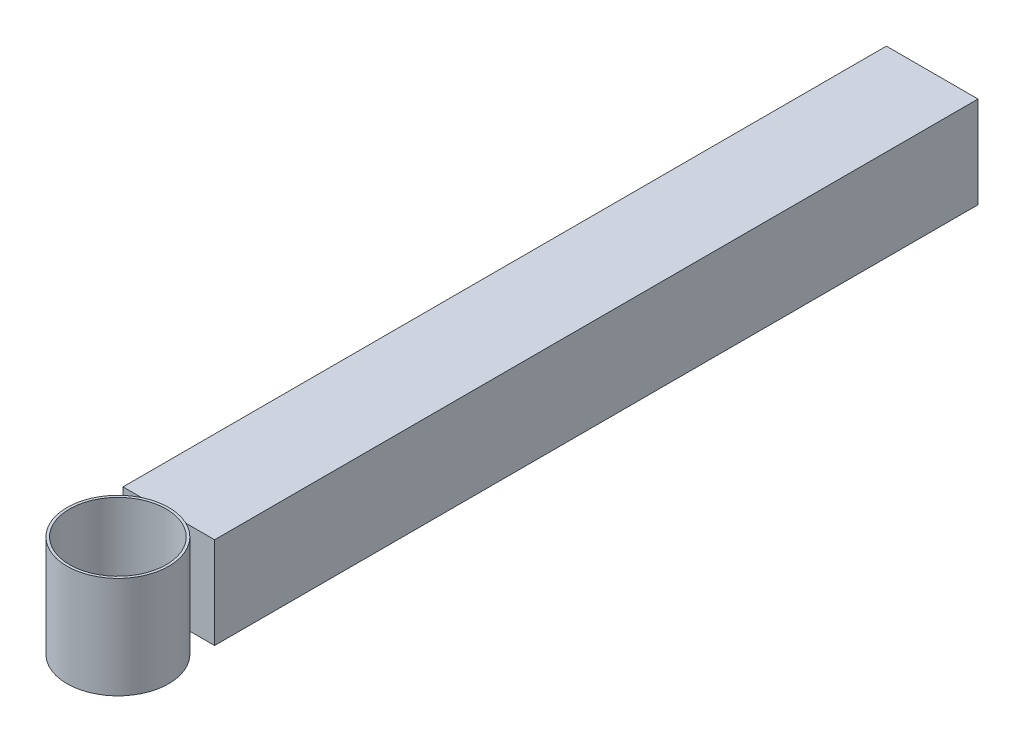
SolidWorks part; units mm, degrees
ref_plane "Front Plane" through (0, 0, 0) normal (0, 0, 1) x (1, 0, 0)
ref_plane "Top Plane" through (0, 0, 0) normal (0, 1, 0) x (1, 0, 0)
ref_plane "Right Plane" through (0, 0, 0) normal (1, 0, 0) x (0, 0, -1)
sketch "Sketch1" plane through (0, 0, 0) normal (0, 0, 1) x (1, 0, 0)
  line L1 (-18, -18) -> (18, -18)
  line L2 (-18, -18) -> (-18, 18)
  line L3 (-18, 18) -> (18, 18)
  line L4 (18, -18) -> (18, 18)
  line L5 (-18, -18) -> (18, 18) construction
  line L6 (-18, 18) -> (18, -18) construction
  point P0 (0, 0)
  dimension "D1" = 36
extrude "Boss-Extrude1" add sketch "Sketch1" along normal blind 300
sketch "Sketch2" plane through (0, 0, 0) normal (0, 1, 0) x (1, 0, 0)
  line L5 (18, -300) -> (-18, -300) construction
  circle A0 centre (0, -320) radius 20
  circle A1 centre (0, -320) radius 19
  dimension "D1" = 40
  dimension "D2" = 1
extrude "Boss-Extrude2" add sketch "Sketch2" along normal blind 20 and the other way blind 20
